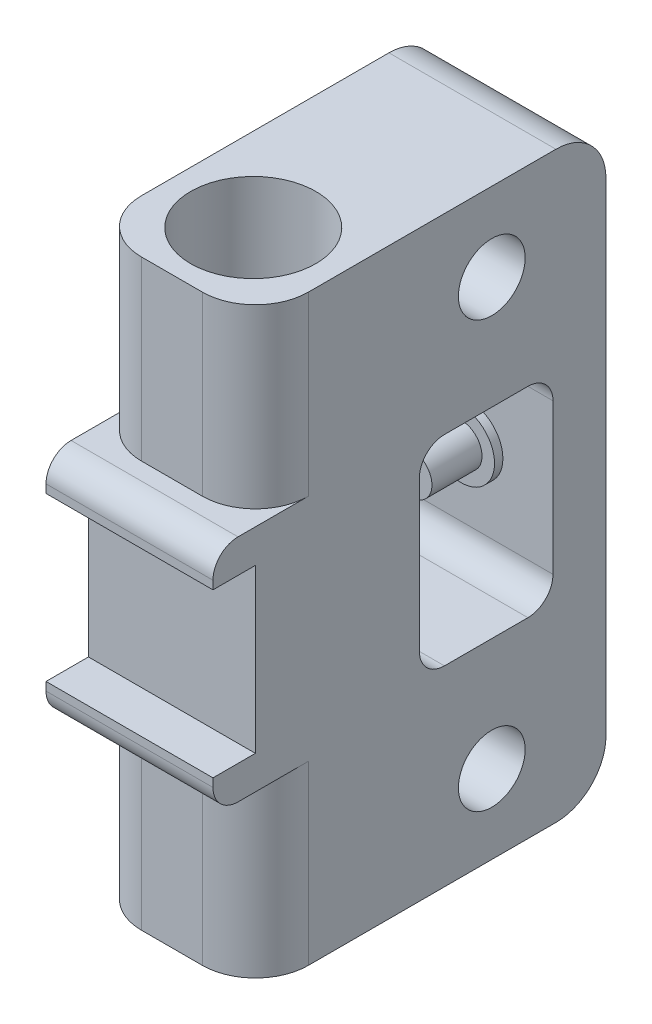
SolidWorks part; units mm, degrees
material "ABS"
ref_plane "Front Plane" through (0, 0, 0) normal (0, 0, 1) x (1, 0, 0)
ref_plane "Top Plane" through (0, 0, 0) normal (0, 1, 0) x (1, 0, 0)
ref_plane "Right Plane" through (0, 0, 0) normal (1, 0, 0) x (0, 0, -1)
sketch "Sketch1" plane through (0, 0, 0) normal (0, 1, 0) x (1, 0, 0)
  line L1 (-10, -21) -> (10, -21)
  line L2 (-10, -21) -> (-10, 21)
  line L3 (-10, 21) -> (10, 21)
  line L4 (10, -21) -> (10, 21)
  line L5 (-10, -21) -> (10, 21) construction
  line L6 (-10, 21) -> (10, -21) construction
  point P0 (0, 0)
  dimension "D1" = 20
  dimension "D2" = 42
extrude "Boss-Extrude1" add sketch "Sketch1" along normal blind 69.85
fillet "Fillet1" radius 6.35 2 edges at (10, 34.925, 21) (-10, 34.925, 21)
sketch "Sketch3" plane through (0, 0, -21) normal (0, 0, -1) x (-1, 0, 0)
  line L0 (-10, 69.85) -> (10, 0) construction
  line L1 (10, 0) -> (-10, 0) construction
  line L2 (-10, 0) -> (10, 69.85) construction
  line L4 (-21, 13.925) -> (21, 13.925)
  line L5 (-21, 13.925) -> (-21, 55.925)
  line L6 (-21, 55.925) -> (21, 55.925)
  line L7 (21, 13.925) -> (21, 55.925)
  line L8 (-21, 13.925) -> (21, 55.925) construction
  line L9 (-21, 55.925) -> (21, 13.925) construction
  point P4 (0, 34.925)
  dimension "D1" = 42
  dimension "D2" = 42
extrude "Boss-Extrude2" add sketch "Sketch3" against normal blind 6.35
sketch "Sketch4" plane through (10, 0, 0) normal (1, 0, 0) x (0, 0, -1)
  line L0 (14.65, 34.925) -> (-14.65, 34.925) construction
  line L2 (14.65, 13.925) -> (14.65, 55.925) construction
  line L3 (-14.65, 69.85) -> (-14.65, 0) construction
  line L5 (-1.35, 22.925) -> (14.65, 22.925)
  line L6 (-1.35, 22.925) -> (-1.35, 46.925)
  line L7 (-1.35, 46.925) -> (14.65, 46.925)
  line L8 (14.65, 22.925) -> (14.65, 46.925)
  line L9 (-1.35, 22.925) -> (14.65, 46.925) construction
  line L10 (-1.35, 46.925) -> (14.65, 22.925) construction
  point P6 (6.65, 34.925)
  dimension "D1" = 24
  dimension "D2" = 16
extrude "Cut-Extrude2" cut sketch "Sketch4" against normal through all
sketch "Sketch6" plane through (0, 0, -21) normal (0, 0, -1) x (-1, 0, 0)
  line L0 (-21, 55.925) -> (21, 13.925) construction
  line L1 (21, 13.925) -> (-21, 13.925) construction
  line L2 (-21, 13.925) -> (21, 55.925) construction
sketch "Sketch8" plane through (10, 0, 0) normal (1, 0, 0) x (0, 0, -1)
  line L0 (21, 34.925) -> (-14.65, 34.925) construction
  line L1 (21, 13.925) -> (21, 55.925) construction
  line L2 (-14.65, 69.85) -> (-14.65, 0) construction
  circle A0 centre (7.3182, 60.425) radius 4
  circle A1 centre (7.3182, 9.425) radius 4
  dimension "D1" = 8
  dimension "D2" = 25.5
extrude "Cut-Extrude5" cut sketch "Sketch8" against normal through all
fillet "Fillet2" radius 6 2 edges at (0, 69.85, -21) (0, 0, -21)
fillet "Fillet3" radius 4 4 edges at (21, 13.925, -17.825) (21, 55.925, -17.825) (-21, 13.925, -17.825) (-21, 55.925, -17.825)
fillet "Fillet4" radius 3 4 edges at (0, 46.925, -14.65) (0, 46.925, 1.35) (0, 22.925, 1.35) (0, 22.925, -14.65)
sketch "Sketch9" plane through (0, 0, -21) normal (0, 0, -1) x (-1, 0, 0)
  line L1 (-10, 13.925) -> (-21, 13.925)
  line L2 (-10, 13.925) -> (-10, 55.925)
  line L3 (-10, 55.925) -> (-21, 55.925)
  line L4 (-21, 13.925) -> (-21, 55.925)
  line L5 (21, 55.925) -> (10, 55.925)
  line L6 (21, 55.925) -> (21, 13.925)
  line L7 (21, 13.925) -> (10, 13.925)
  line L8 (10, 55.925) -> (10, 13.925)
extrude "Cut-Extrude6" cut sketch "Sketch9" against normal through all
sketch "Sketch10" plane through (0, 0, -14.65) normal (0, 0, 1) x (1, 0, 0)
  line L0 (-10, 43.925) -> (10, 25.925) construction
  circle A0 centre (0, 34.925) radius 4
  dimension "D1" = 8
extrude "Boss-Extrude3" add sketch "Sketch10" along normal blind 1
sketch "Sketch11" plane through (0, 0, -13.65) normal (0, 0, 1) x (1, 0, 0)
  circle A0 centre (0, 34.925) radius 2.5
  dimension "D1" = 5
extrude "Boss-Extrude4" add sketch "Sketch11" along normal blind 6
sketch "Sketch12" plane through (0, 0, 21) normal (0, 0, 1) x (1, 0, 0)
  line L0 (0, 0) -> (0, 69.85) construction
  line L1 (-3.65, 0) -> (3.65, 0) construction
  line L2 (-3.65, 69.85) -> (3.65, 69.85) construction
  line L3 (-10, 0) -> (-10, 69.85) construction
  line L4 (10, 21.175) -> (-10, 21.175)
  line L5 (10, 21.175) -> (10, 48.675)
  line L6 (10, 48.675) -> (-10, 48.675)
  line L7 (-10, 21.175) -> (-10, 48.675)
  line L8 (10, 21.175) -> (-10, 48.675) construction
  line L9 (10, 48.675) -> (-10, 21.175) construction
  point P6 (0, 34.925)
  dimension "D1" = 27.5
extrude "Boss-Extrude5" add sketch "Sketch12" against normal blind 6.35
sketch "Sketch13" plane through (0, 0, 21) normal (0, 0, 1) x (1, 0, 0)
  line L0 (-10, 34.925) -> (10, 34.925) construction
  line L1 (-10, 48.675) -> (-10, 21.175) construction
  line L2 (10, 21.175) -> (10, 48.675) construction
  line L3 (10, 48.675) -> (10, 44.675)
  line L4 (-10, 21.175) -> (10, 21.175)
  line L5 (-10, 21.175) -> (-10, 25.175)
  line L6 (-10, 25.175) -> (10, 25.175)
  line L7 (10, 21.175) -> (10, 25.175)
  line L8 (-10, 44.675) -> (10, 44.675)
  line L9 (-10, 48.675) -> (-10, 44.675)
  line L10 (-10, 48.675) -> (10, 48.675)
  dimension "D1" = 4
extrude "Boss-Extrude6" add sketch "Sketch13" along normal blind 5.08
sketch "Sketch2" plane through (0, 69.85, 0) normal (0, 1, 0) x (1, 0, 0)
  circle A0 centre (0, -11.2544) radius 7.5
  dimension "D1" = 15
extrude "Cut-Extrude1" cut sketch "Sketch2" against normal through all
fillet "Fillet5" radius 3 2 edges at (0, 48.675, 26.08) (0, 21.175, 26.08)
